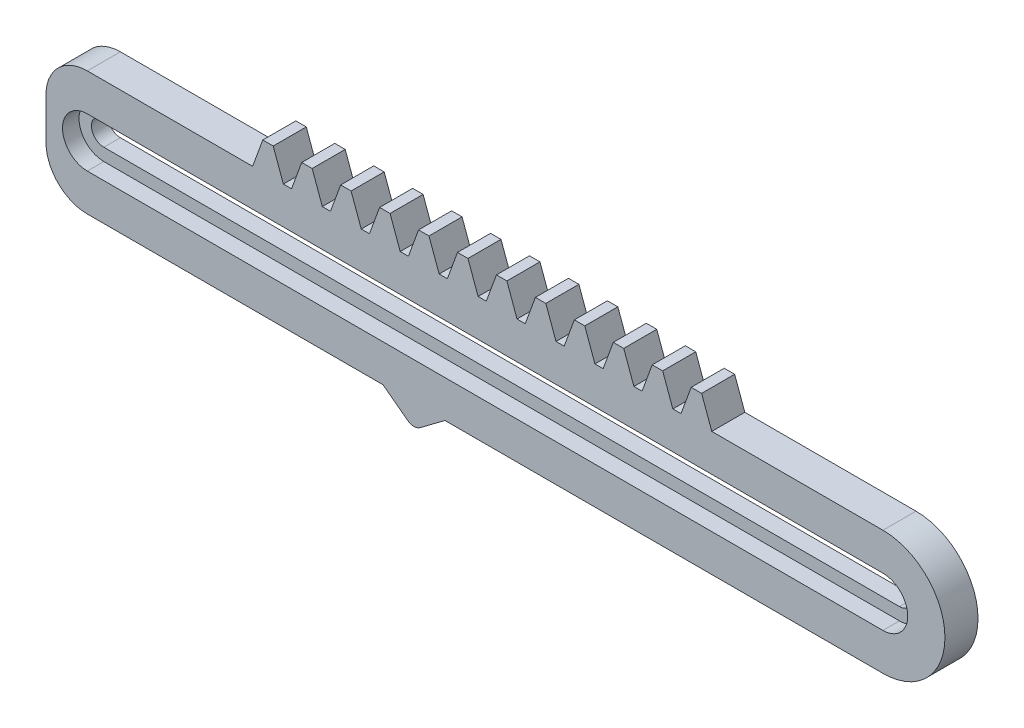
SolidWorks part; units mm, degrees
ref_plane "Plan de face" through (0, 0, 0) normal (0, 0, 1) x (1, 0, 0)
ref_plane "Plan de dessus" through (0, 0, 0) normal (0, 1, 0) x (1, 0, 0)
ref_plane "Plan de droite" through (0, 0, 0) normal (1, 0, 0) x (0, 0, -1)
sketch "Esquisse1" plane through (0, 0, 0) normal (0, 0, 1) x (1, 0, 0)
  line L0 (0, 7.8686) -> (0, 35.51) construction
  line L1 (3.7211, 15) -> (1.2643, 21.75)
  line L2 (-53.7211, 15) -> (-53.7211, -15)
  line L3 (-3.7211, 15) -> (-1.2643, 21.75)
  line L4 (-1.2643, 21.75) -> (1.2643, 21.75)
  line L5 (3.7211, 15) -> (5.7037, 15)
  line L6 (-2.3562, 18.75) -> (0, 18.75) construction
  line L7 (107.3936, 15) -> (148.8231, 15)
  line L8 (-3.7211, 15) -> (-53.7211, 15)
  line L9 (-43.7211, 3) -> (148.8231, 3)
  line L10 (-43.7211, -3) -> (148.8231, -3)
  line L11 (-53.7211, -15) -> (27.8231, -15)
  line L12 (148.8231, -15) -> (148.8231, -20) construction
  line L13 (148.8231, -20) -> (35.3231, -20) construction
  line L14 (35.3231, -20) -> (35.3231, -15) construction
  line L15 (35.3231, -20) -> (32.8231, -20) construction
  line L16 (32.8231, -20) -> (24.3231, -20) construction
  line L17 (27.8231, -15) -> (33.8231, -19.5)
  line L18 (32.8231, -20) -> (32.8231, -18.75) construction
  line L19 (13.1459, 15) -> (10.6891, 21.75)
  line L20 (13.1459, 15) -> (15.1285, 15)
  line L21 (5.7037, 15) -> (8.1605, 21.75)
  line L22 (8.1605, 21.75) -> (10.6891, 21.75)
  line L23 (22.5706, 15) -> (24.5533, 15)
  line L24 (7.0686, 18.75) -> (9.4248, 18.75) construction
  line L25 (22.5706, 15) -> (20.1138, 21.75)
  line L26 (31.9954, 15) -> (33.978, 15)
  line L27 (15.1285, 15) -> (17.5853, 21.75)
  line L28 (17.5853, 21.75) -> (20.1138, 21.75)
  line L29 (41.4202, 15) -> (43.4028, 15)
  line L30 (16.4934, 18.75) -> (18.8496, 18.75) construction
  line L31 (31.9954, 15) -> (29.5386, 21.75)
  line L32 (50.845, 15) -> (52.8276, 15)
  line L33 (24.5533, 15) -> (27.0101, 21.75)
  line L34 (27.0101, 21.75) -> (29.5386, 21.75)
  line L35 (60.2698, 15) -> (62.2524, 15)
  line L36 (25.9181, 18.75) -> (28.2743, 18.75) construction
  line L37 (41.4202, 15) -> (38.9634, 21.75)
  line L38 (69.6945, 15) -> (71.6771, 15)
  line L39 (33.978, 15) -> (36.4348, 21.75)
  line L40 (36.4348, 21.75) -> (38.9634, 21.75)
  line L41 (79.1193, 15) -> (81.1019, 15)
  line L42 (35.3429, 18.75) -> (37.6991, 18.75) construction
  line L43 (50.845, 15) -> (48.3882, 21.75)
  line L44 (88.5441, 15) -> (90.5267, 15)
  line L45 (43.4028, 15) -> (45.8596, 21.75)
  line L46 (45.8596, 21.75) -> (48.3882, 21.75)
  line L47 (97.9689, 15) -> (99.9515, 15)
  line L48 (44.7677, 18.75) -> (47.1239, 18.75) construction
  line L49 (60.2698, 15) -> (57.813, 21.75)
  line L51 (52.8276, 15) -> (55.2844, 21.75)
  line L52 (55.2844, 21.75) -> (57.813, 21.75)
  line L54 (54.1925, 18.75) -> (56.5487, 18.75) construction
  line L55 (69.6945, 15) -> (67.2377, 21.75)
  line L57 (62.2524, 15) -> (64.7092, 21.75)
  line L58 (64.7092, 21.75) -> (67.2377, 21.75)
  line L59 (42.8231, -15) -> (36.8231, -19.5)
  line L60 (63.6173, 18.75) -> (65.9734, 18.75) construction
  line L61 (79.1193, 15) -> (76.6625, 21.75)
  line L62 (42.8231, -15) -> (148.8231, -15)
  line L63 (71.6771, 15) -> (74.1339, 21.75)
  line L64 (74.1339, 21.75) -> (76.6625, 21.75)
  line L66 (73.042, 18.75) -> (75.3982, 18.75) construction
  line L67 (88.5441, 15) -> (86.0873, 21.75)
  line L69 (81.1019, 15) -> (83.5587, 21.75)
  line L70 (83.5587, 21.75) -> (86.0873, 21.75)
  line L72 (82.4668, 18.75) -> (84.823, 18.75) construction
  line L73 (97.9689, 15) -> (95.5121, 21.75)
  line L75 (90.5267, 15) -> (92.9835, 21.75)
  line L76 (92.9835, 21.75) -> (95.5121, 21.75)
  line L78 (91.8916, 18.75) -> (94.2478, 18.75) construction
  line L79 (107.3936, 15) -> (104.9368, 21.75)
  line L81 (99.9515, 15) -> (102.4083, 21.75)
  line L82 (102.4083, 21.75) -> (104.9368, 21.75)
  line L84 (101.3164, 18.75) -> (103.6726, 18.75) construction
  line L104 (148.8231, 0) -> (-14.7124, 0) construction
  line L105 (135.668, 15) -> (133.2112, 21.75) [skipped]
  line L106 (130.6826, 21.75) -> (133.2112, 21.75) [skipped]
  line L107 (129.5907, 18.75) -> (131.9469, 18.75) construction
  line L108 (128.2258, 15) -> (130.6826, 21.75) [skipped]
  line L109 (116.8184, 15) -> (114.3616, 21.75) [skipped]
  line L110 (109.3763, 15) -> (111.8331, 21.75) [skipped]
  line L111 (111.8331, 21.75) -> (114.3616, 21.75) [skipped]
  line L112 (126.2432, 15) -> (123.7864, 21.75) [skipped]
  line L113 (118.801, 15) -> (121.2578, 21.75) [skipped]
  line L114 (110.7411, 18.75) -> (113.0973, 18.75) construction
  line L115 (120.1659, 18.75) -> (122.5221, 18.75) construction
  line L116 (121.2578, 21.75) -> (123.7864, 21.75) [skipped]
  arc A0 (148.8231, 15) -> (148.8231, -15) centre (148.8231, 0) cw
  arc A1 (148.8231, -3) -> (148.8231, 3) centre (148.8231, 0) ccw
  arc A2 (-43.7211, 3) -> (-43.7211, -3) centre (-43.7211, 0) ccw
  arc A3 (33.8231, -19.5) -> (36.8231, -19.5) centre (35.3231, -17.5) ccw
  point P11 (0, 21.75)
  point P13 (122.5221, 21.75)
  point P15 (113.0973, 21.75)
  point P25 (131.9469, 21.75)
  point P35 (9.4248, 21.75)
  point P38 (-53.7211, 0)
  point P44 (18.8496, 21.75)
  point P53 (28.2743, 21.75)
  point P62 (37.6991, 21.75)
  point P71 (47.1239, 21.75)
  point P80 (56.5487, 21.75)
  point P89 (65.9734, 21.75)
  point P98 (75.3982, 21.75)
  point P107 (84.823, 21.75)
  point P116 (94.2478, 21.75)
  point P125 (103.6726, 21.75)
  dimension "D14" = 9.4248
  dimension "D2" = 15
  dimension "D3" = 5
  dimension "D4" = 50
  dimension "D5" = 3
  dimension "D6" = 2.3562
  dimension "D7" = 202.5442
  dimension "D10" = 2.5286
  dimension "D13" = 15
extrude "Boss.-Extru.1" add sketch "Esquisse1" along normal blind 8
sketch "Esquisse2" plane through (0, 0, 8) normal (0, 0, 1) x (1, 0, 0)
  line L1 (-43.7211, 6) -> (148.8231, 6)
  line L2 (-43.7211, -6) -> (148.8231, -6)
  arc A0 (-43.7211, 6) -> (-43.7211, -6) centre (-43.7211, 0) ccw
  arc A1 (148.8231, -6) -> (148.8231, 6) centre (148.8231, 0) ccw
extrude "Enlèv. mat.-Extru.1" cut sketch "Esquisse2" against normal blind 4
fillet "Congé2" radius 10 2 edges at (-53.7211, -15, 4) (-53.7211, 15, 4)
